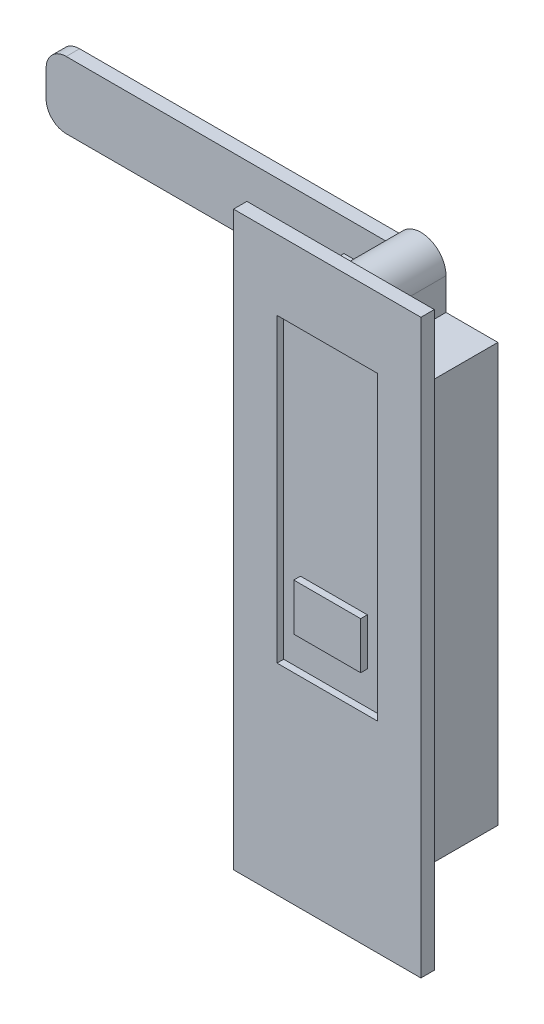
SolidWorks part; units mm, degrees
ref_plane "前视基准面" through (0, 0, 0) normal (0, 0, 1) x (1, 0, 0)
ref_plane "上视基准面" through (0, 0, 0) normal (0, 1, 0) x (1, 0, 0)
ref_plane "右视基准面" through (0, 0, 0) normal (1, 0, 0) x (0, 0, -1)
sketch "草图1" plane through (0, 0, 0) normal (0, 0, 1) x (1, 0, 0)
  line L1 (-14, -42.75) -> (14, -42.75)
  line L2 (-14, -42.75) -> (-14, 42.75)
  line L3 (-14, 42.75) -> (14, 42.75)
  line L4 (14, -42.75) -> (14, 42.75)
  line L5 (-14, -42.75) -> (14, 42.75) construction
  line L6 (-14, 42.75) -> (14, -42.75) construction
  point P0 (0, 0)
  dimension "D1" = 28
  dimension "D2" = 85.5
extrude "凸台-拉伸1" add sketch "草图1" along normal blind 2
sketch "草图2" plane through (0, 0, 2) normal (0, 0, 1) x (1, 0, 0)
  line L0 (0, 42.75) -> (0, -42.75) construction
  line L1 (14, 42.75) -> (-14, 42.75) construction
  line L2 (-14, -42.75) -> (14, -42.75) construction
  line L4 (-7.5, -12.75) -> (7.5, -12.75)
  line L5 (-7.5, -12.75) -> (-7.5, 32.25)
  line L6 (-7.5, 32.25) -> (7.5, 32.25)
  line L7 (7.5, -12.75) -> (7.5, 32.25)
  line L8 (-7.5, -12.75) -> (7.5, 32.25) construction
  line L9 (-7.5, 32.25) -> (7.5, -12.75) construction
  line L10 (-5, -7.75) -> (5, -7.75)
  line L11 (-5, -7.75) -> (-5, -0.75)
  line L12 (-5, -0.75) -> (5, -0.75)
  line L13 (5, -7.75) -> (5, -0.75)
  line L14 (-5, -7.75) -> (5, -0.75) construction
  line L15 (-5, -0.75) -> (5, -7.75) construction
  point P6 (0, 9.75)
  point P11 (-5.1679, -1.6169)
  point P12 (0, -4.25)
  dimension "D1" = 15
  dimension "D2" = 45
  dimension "D3" = 30
  dimension "D4" = 10
  dimension "D5" = 7
  dimension "D6" = 5
extrude "切除-拉伸1" cut sketch "草图2" against normal blind 1
sketch "草图3" plane through (0, 0, 0) normal (0, 0, -1) x (-1, 0, 0)
  line L0 (0, 42.75) -> (0, -42.75) construction
  line L1 (-14, 42.75) -> (14, 42.75) construction
  line L2 (14, -42.75) -> (-14, -42.75) construction
  line L3 (0, -36) -> (0, 36) construction
  line L4 (-11.5, -31.25) -> (11.5, -31.25)
  line L5 (-11.5, -31.25) -> (-11.5, 31.25)
  line L6 (-11.5, 31.25) -> (11.5, 31.25)
  line L7 (11.5, -31.25) -> (11.5, 31.25)
  line L8 (-11.5, -31.25) -> (11.5, 31.25) construction
  line L9 (-11.5, 31.25) -> (11.5, -31.25) construction
  line L10 (-3.75, -36) -> (-3.75, 36)
  line L11 (3.75, -36) -> (3.75, 36)
  arc A0 (-3.75, -36) -> (3.75, -36) centre (0, -36) ccw
  arc A1 (3.75, 36) -> (-3.75, 36) centre (0, 36) ccw
  point P6 (0, 0)
  point P14 (0, 0)
  dimension "D1" = 23
  dimension "D2" = 62.5
  dimension "D3" = 7.5
  dimension "D4" = 72
extrude "凸台-拉伸2" add sketch "草图3" along normal blind 12 contours L4 L11 L6 L10 | L4 L10 L6 L5 | L11 L4 L7 L6 | L11 A1 L10 L6 | L10 A0 L11 L4
sketch "草图4" plane through (0, 0, -12) normal (0, 0, -1) x (-1, 0, 0)
  line L0 (0, 36) -> (53, 36)
  line L1 (56, 33) -> (56, 29)
  line L2 (53, 26) -> (0, 26)
  line L3 (0, 26) -> (0, 36)
  arc A0 (56, 29) -> (53, 26) centre (53, 29) cw
  arc A1 (56, 33) -> (53, 36) centre (53, 33) ccw
  point P7 (56, 26)
  point P10 (56, 36)
  dimension "D3" = 3
  dimension "D1" = 56
  dimension "D2" = 10
extrude "凸台-拉伸3" add sketch "草图4" along normal blind 2
